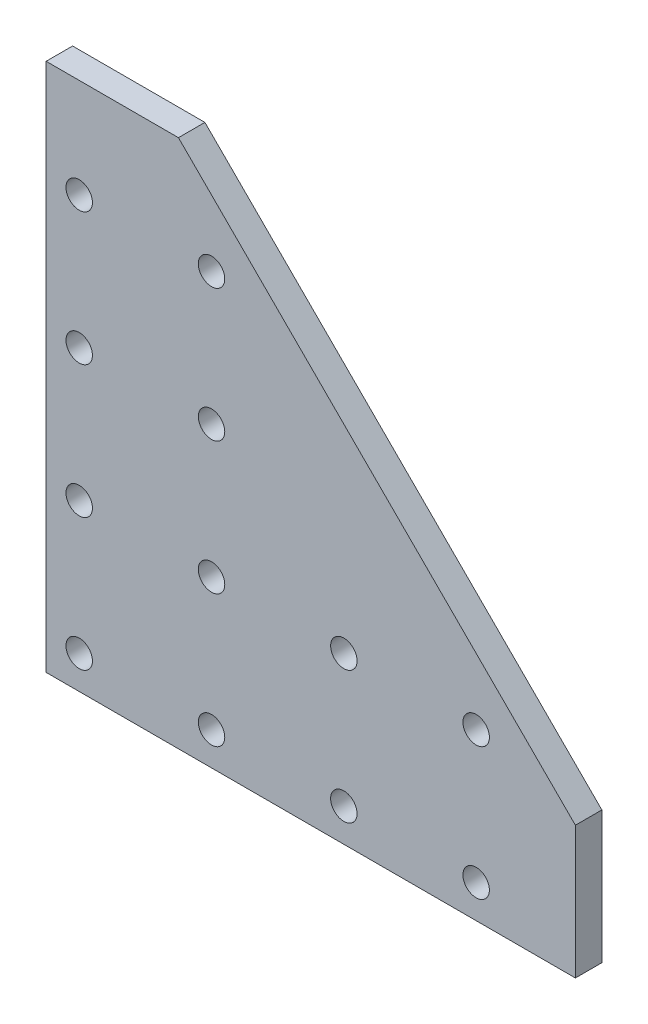
SolidWorks part; units mm, degrees
ref_plane "Front Plane" through (0, 0, 0) normal (0, 0, 1) x (1, 0, 0)
ref_plane "Top Plane" through (0, 0, 0) normal (0, 1, 0) x (1, 0, 0)
ref_plane "Right Plane" through (0, 0, 0) normal (1, 0, 0) x (0, 0, -1)
sketch "Sketch1" plane through (0, 0, 0) normal (0, 0, 1) x (1, 0, 0)
  line L0 (0, 0) -> (0, 160)
  line L1 (0, 160) -> (40, 160)
  line L2 (40, 160) -> (160, 40)
  line L3 (160, 40) -> (160, 0)
  line L4 (160, 0) -> (0, 0)
  line L5 (10, 121.4809) -> (10, 10) construction
  line L6 (118.2153, 10) -> (10, 10) construction
  line L7 (10, 10) -> (74.1077, 74.1077) construction
  line L9 (160, 20) -> (108.4128, 20) construction
  circle A0 centre (10, 10) radius 4
  circle A1 centre (50, 10) radius 4
  circle A2 centre (90, 10) radius 4
  circle A3 centre (10, 90) radius 4
  circle A4 centre (10, 50) radius 4
  circle A5 centre (130, 10) radius 4
  circle A9 centre (10, 130) radius 4
  circle A18 centre (130, 50) radius 4
  circle A19 centre (90, 50) radius 4
  circle A20 centre (50, 50) radius 4
  circle A21 centre (50, 130) radius 4
  circle A22 centre (50, 90) radius 4
  dimension "D4" = 8
  dimension "D5" = 40
  dimension "D6" = 40
  dimension "D9" = 40
  dimension "D10" = 40
  dimension "D11" = 2
  dimension "D12" = 2
  dimension "D1" = 45
  dimension "D2" = 160
  dimension "D3" = 40
  dimension "D7" = 10
  dimension "D8" = 10
extrude "Boss-Extrude1" add sketch "Sketch1" along normal blind 8
